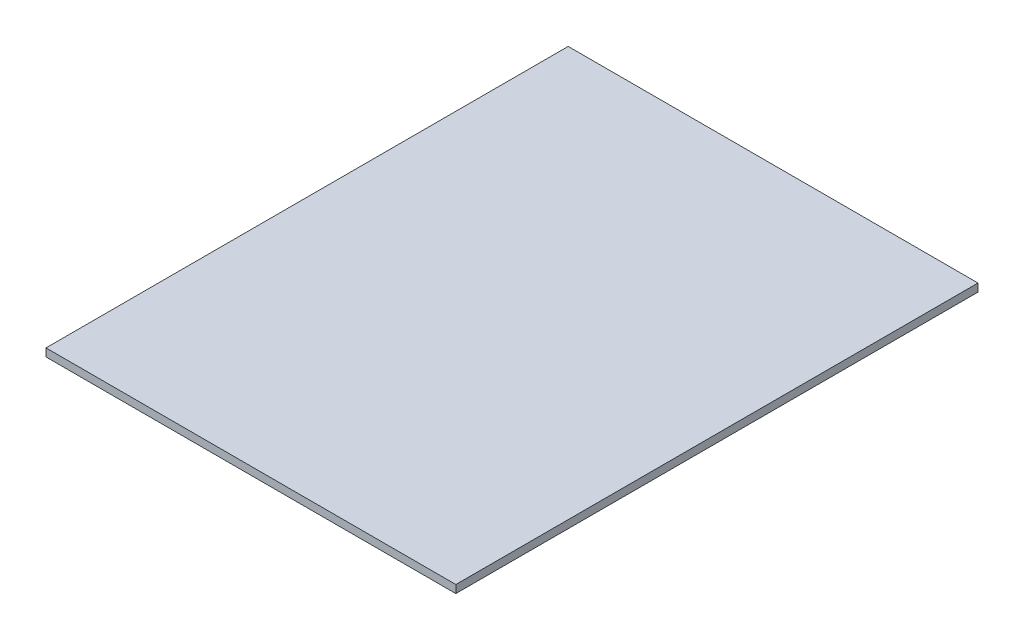
SolidWorks part; units mm, degrees
ref_plane "Front Plane" through (0, 0, 0) normal (0, 0, 1) x (1, 0, 0)
ref_plane "Top Plane" through (0, 0, 0) normal (0, 1, 0) x (1, 0, 0)
ref_plane "Right Plane" through (0, 0, 0) normal (1, 0, 0) x (0, 0, -1)
sketch "Sketch1" plane through (0, -2.1, 0) normal (0, -1, 0) x (1, 0, 0)
  line L1 (-52.05, 66.32) -> (52.05, 66.32)
  line L2 (-52.05, 66.32) -> (-52.05, -66.32)
  line L3 (-52.05, -66.32) -> (52.05, -66.32)
  line L4 (52.05, 66.32) -> (52.05, -66.32)
extrude "Boss-Extrude1" add sketch "Sketch1" along normal blind 2
